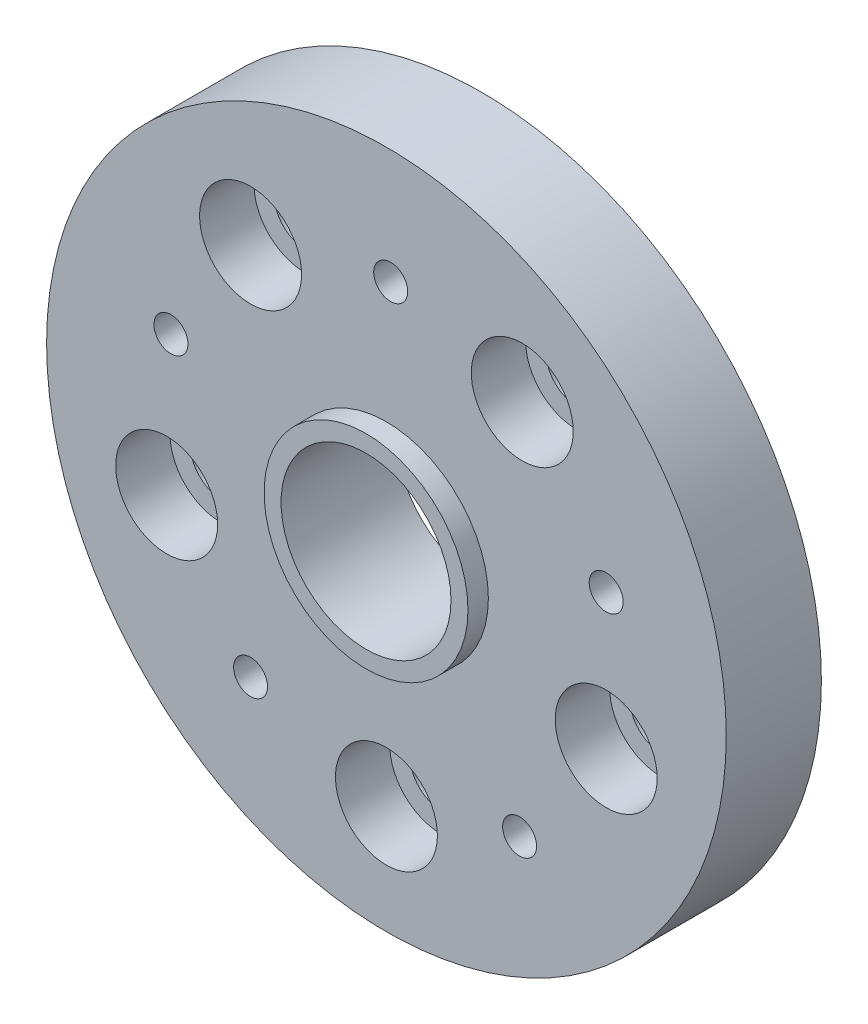
SolidWorks part; units mm, degrees
material "6061-T6 (SS)"
ref_plane "Front Plane" through (0, 0, 0) normal (0, 0, 1) x (1, 0, 0)
ref_plane "Top Plane" through (0, 0, 0) normal (0, 1, 0) x (1, 0, 0)
ref_plane "Right Plane" through (0, 0, 0) normal (1, 0, 0) x (0, 0, -1)
sketch "Sketch1" plane through (0, 0, 0) normal (0, 0, 1) x (1, 0, 0)
  circle A0 centre (0, 0) radius 50
  dimension "D1" = 100
extrude "Boss-Extrude1" add sketch "Sketch1" along normal blind 14
sketch "Sketch2" plane through (0, 0, 14) normal (0, 0, 1) x (1, 0, 0)
  circle A0 centre (0, 0) radius 12.5
  dimension "D1" = 25
extrude "Cut-Extrude1" cut sketch "Sketch2" against normal through all
sketch "Sketch3" plane through (0, 0, 14) normal (0, 0, 1) x (1, 0, 0)
  circle A0 centre (0, 0) radius 15
  circle A1 centre (0, 0) radius 12.5
  circle A2 centre (0, 0) radius 12.5 construction
  dimension "D1" = 2.5
extrude "Boss-Extrude2" add sketch "Sketch3" along normal blind 3
hole_wizard "CBORE for M8 SHCS1" positions "Sketch6" profile "Sketch7" counterbore size "M8" standard "ANSI Metric" end condition through all
sketch "Sketch6" plane through (0, 0, 14) normal (0, 0, 1) x (1, 0, 0)
  line L0 (0, 0) -> (0, -34) construction
  point P0 (0, -34)
  point P15 (-32.3359, -10.5066)
  point P16 (-19.9847, 27.5066)
  point P17 (19.9847, 27.5066)
  point P18 (32.3359, -10.5066)
  dimension "D1" = 34
  dimension "D2" = 5
sketch "Sketch7" plane through (0, -34, 14) normal (1, 0, 0) x (0, -1, 0)
  line L0 (0, 0) -> (0, 14)
  line L1 (0, 14) -> (4.5, 14)
  line L3 (4.5, 14) -> (4.5, 8)
  line L4 (4.5, 8) -> (7.5, 8)
  line L5 (7.5, 8) -> (7.5, 0)
  line L7 (7.5, 0) -> (0, 0)
  line L11 (0, -6.35) -> (0, 107.95) construction
  dimension "Thru Hole Dia." = 9
  dimension "Thru Hole Depth" = 14
  dimension "C'Bore Dia." = 15
  dimension "C'Bore Depth" = 8
hole_wizard "M6x1.0 Tapped Hole1" positions "Sketch8" profile "Sketch9" tap size "M6x1.0" standard "ANSI Metric" end condition through all
sketch "Sketch8" plane through (0, 0, 14) normal (0, 0, 1) x (1, 0, 0)
  line L0 (0, 0) -> (0, -34) construction
  line L1 (0, 0) -> (-19.9847, -27.5066) construction
  point P0 (-19.9847, -27.5066)
  point P20 (-31.7058, 10.3019)
  point P21 (0.6301, 33.1328)
  point P22 (32.3359, 9.4346)
  point P23 (19.5953, -28.0426)
  point P24 (0.1741, -0.536)
  dimension "D1" = 36
  dimension "D2" = 5
sketch "Sketch9" plane through (-19.9847, -27.5066, 14) normal (1, 0, 0) x (0, -1, 0)
  line L0 (0, 0) -> (0, 14)
  line L1 (0, 14) -> (2.5, 14)
  line L2 (2.5, 14) -> (2.5, 0)
  line L5 (2.5, 0) -> (0, 0)
  line L11 (0, -6.35) -> (0, 107.95) construction
  dimension "Thru Tap Drill Dia." = 5
  dimension "Thru Tap Drill Depth" = 14
cosmetic thread "Hole Thread1"
cosmetic thread "Hole Thread2"
cosmetic thread "Hole Thread3"
cosmetic thread "Hole Thread4"
cosmetic thread "Hole Thread5"
